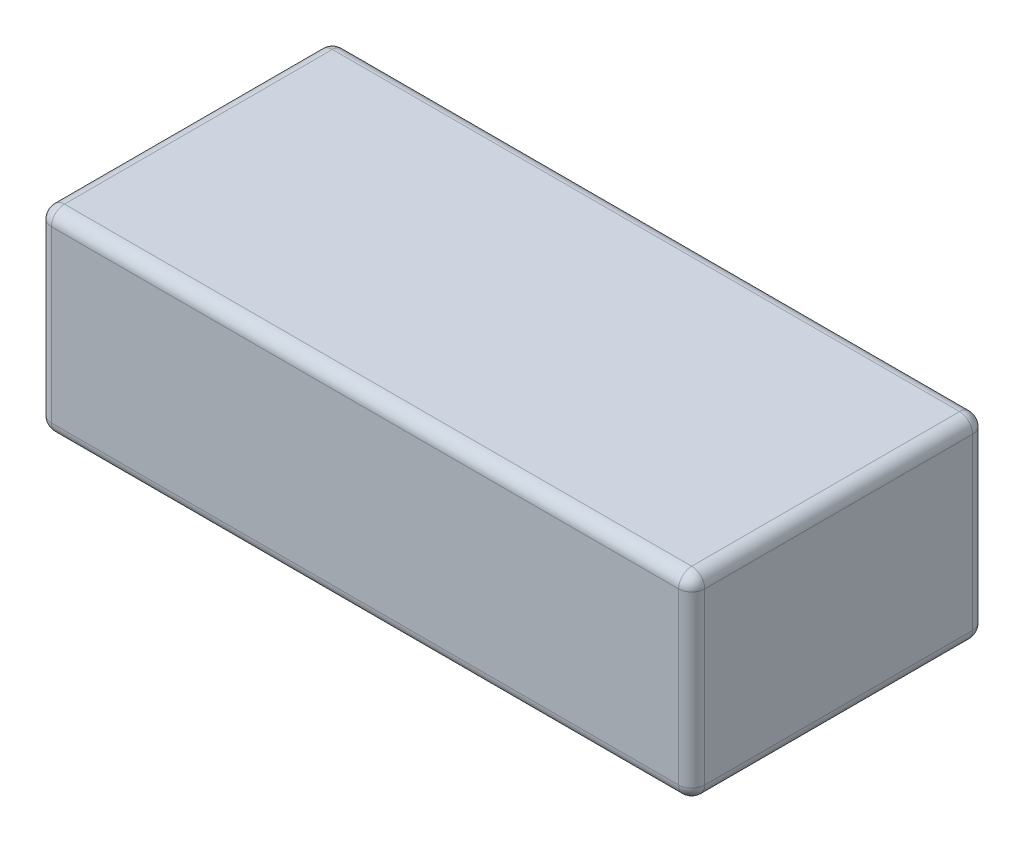
SolidWorks part; units mm, degrees
ref_plane "Front Plane" through (0, 0, 0) normal (0, 0, 1) x (1, 0, 0)
ref_plane "Top Plane" through (0, 0, 0) normal (0, 1, 0) x (1, 0, 0)
ref_plane "Right Plane" through (0, 0, 0) normal (1, 0, 0) x (0, 0, -1)
sketch "Sketch1" plane through (0, 0, 0) normal (0, 1, 0) x (1, 0, 0)
  line L1 (0, 0) -> (100, 0)
  line L2 (0, 0) -> (0, 45)
  line L3 (0, 45) -> (100, 45)
  line L4 (100, 0) -> (100, 45)
  dimension "D1" = 100
  dimension "D2" = 45
extrude "Boss-Extrude1" add sketch "Sketch1" along normal blind 30
fillet "Fillet1" radius 2 12 edges at (100, 0, -22.5) (0, 0, -22.5) (100, 15, -45) (0, 15, -45) (50, 0, -45) (50, 30, -45) (100, 30, -22.5) (0, 30, -22.5) (0, 15, 0) (50, 30, 0) (100, 15, 0) (50, 0, 0)
